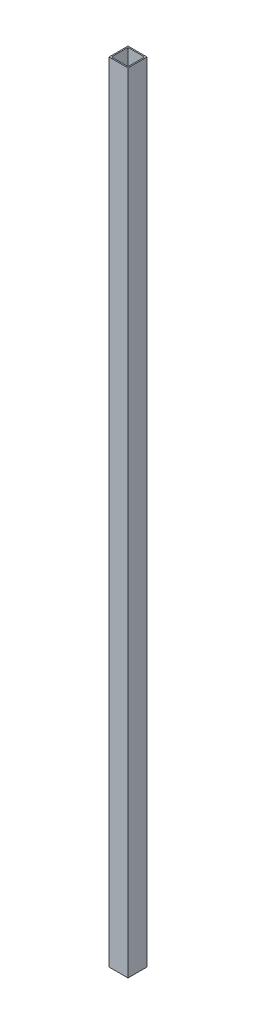
SolidWorks part; units mm, degrees
material "6061 Alloy"
ref_plane "Front Plane" through (0, 0, 0) normal (0, 0, 1) x (1, 0, 0)
ref_plane "Top Plane" through (0, 0, 0) normal (0, 1, 0) x (1, 0, 0)
ref_plane "Right Plane" through (0, 0, 0) normal (1, 0, 0) x (0, 0, -1)
sketch "Sketch1" plane through (0, 0, 0) normal (0, 1, 0) x (1, 0, 0)
  line L1 (12.7, 12.7) -> (-12.7, 12.7)
  line L2 (12.7, 12.7) -> (12.7, -12.7)
  line L3 (12.7, -12.7) -> (-12.7, -12.7)
  line L4 (-12.7, 12.7) -> (-12.7, -12.7)
  line L5 (12.7, 12.7) -> (-12.7, -12.7) construction
  line L6 (12.7, -12.7) -> (-12.7, 12.7) construction
  line L7 (11.1125, 11.1125) -> (-11.1125, 11.1125)
  line L8 (11.1125, 11.1125) -> (11.1125, -11.1125)
  line L9 (11.1125, -11.1125) -> (-11.1125, -11.1125)
  line L10 (-11.1125, 11.1125) -> (-11.1125, -11.1125)
  line L11 (11.1125, 11.1125) -> (-11.1125, -11.1125) construction
  line L12 (11.1125, -11.1125) -> (-11.1125, 11.1125) construction
  point P0 (0, 0)
  point P6 (0, 0)
  dimension "D1" = 25.4
  dimension "D2" = 25.4
  dimension "D3" = 1.5875
  dimension "D4" = 1.5875
extrude "Boss-Extrude1" add sketch "Sketch1" along normal blind 1054.1
